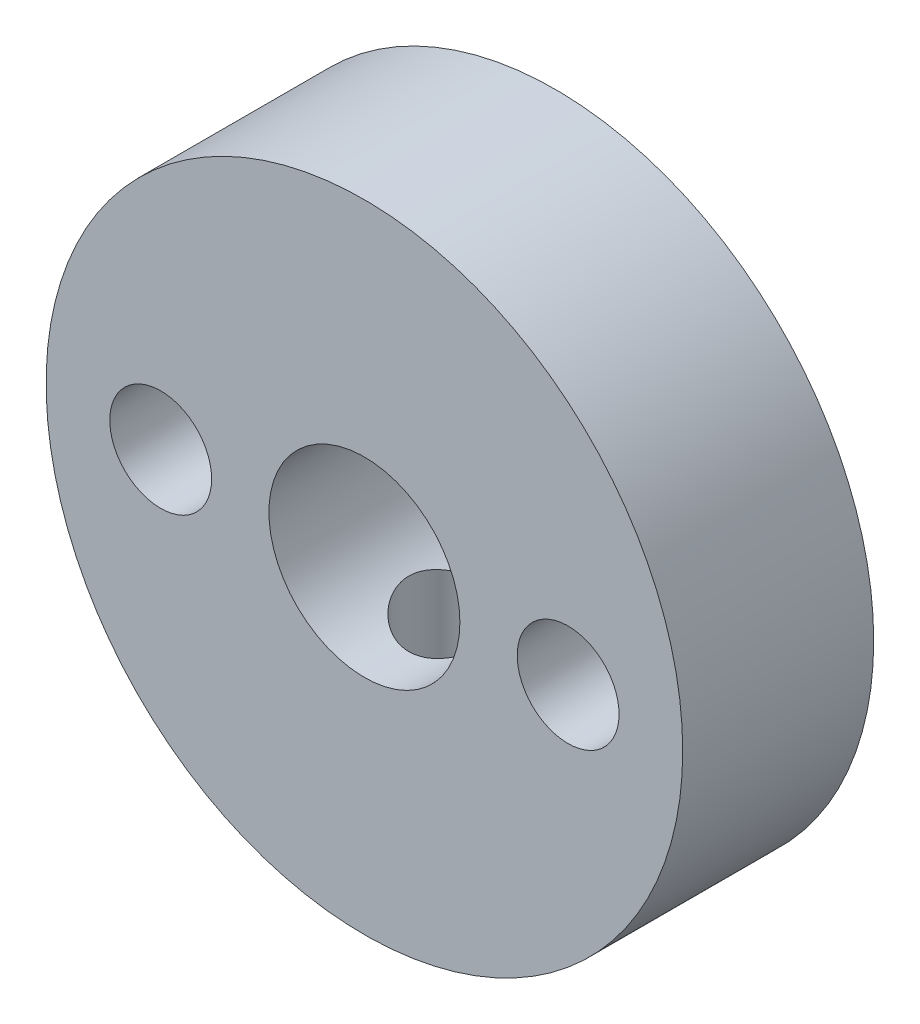
SolidWorks part; units mm, degrees
ref_plane "Front Plane" through (0, 0, 0) normal (0, 0, 1) x (1, 0, 0)
ref_plane "Top Plane" through (0, 0, 0) normal (0, 1, 0) x (1, 0, 0)
ref_plane "Right Plane" through (0, 0, 0) normal (1, 0, 0) x (0, 0, -1)
sketch "Sketch1" plane through (0, 0, 0) normal (0, 0, 1) x (1, 0, 0)
  circle A0 centre (0, 0) radius 5
  circle A1 centre (0, 0) radius 1.5
extrude "Extrude1" add sketch "Sketch1" along normal mid plane 3
sketch "Sketch2" plane through (0, 0, 0) normal (0, 0, 1) x (1, 0, 0)
  circle A0 centre (0, 0) radius 3.2 construction
  circle A1 centre (-3.2, 0) radius 0.8
  circle A4 centre (3.2, 0) radius 0.8
  circle A6 centre (0, -3.2) radius 0.8 [skipped]
  circle A7 centre (0, 3.2) radius 0.8 [skipped]
  dimension "D1" = 4
extrude "Extrude2" cut sketch "Sketch2" against normal through all both and the other way through all
sketch "Sketch3" plane through (0, 0, 0) normal (0, 1, 0) x (1, 0, 0)
  circle A0 centre (0, 0) radius 0.8
extrude "Extrude3" cut sketch "Sketch3" against normal through all
